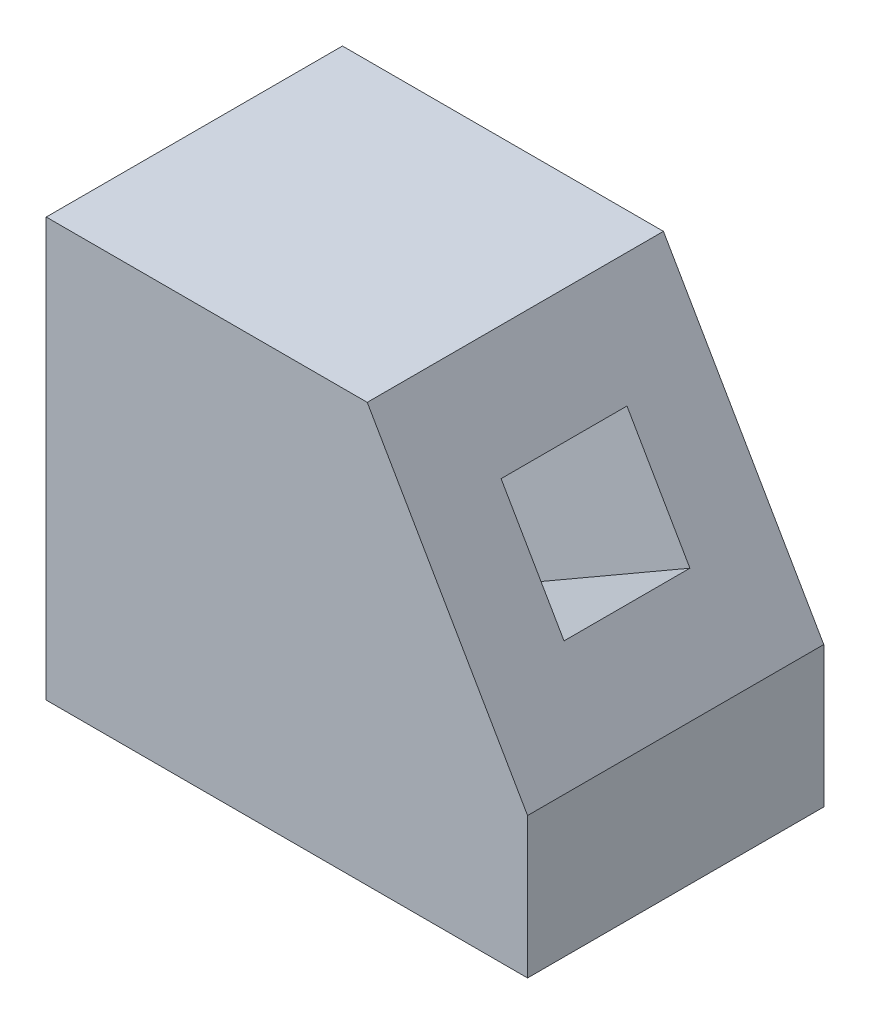
SolidWorks part; units mm, degrees
ref_plane "前视基准面" through (0, 0, 0) normal (0, 0, 1) x (1, 0, 0)
ref_plane "上视基准面" through (0, 0, 0) normal (0, 1, 0) x (1, 0, 0)
ref_plane "右视基准面" through (0, 0, 0) normal (1, 0, 0) x (0, 0, -1)
other "Configuration Table"
sketch "草图1" plane through (0, 0, 0) normal (0, 1, 0) x (1, 0, 0)
  line L0 (6.5, 0) -> (6.5, 8) construction
  line L1 (0, 0) -> (13, 0)
  line L2 (0, 0) -> (0, 8)
  line L3 (0, 8) -> (13, 8)
  line L4 (13, 0) -> (13, 8)
  dimension "D1" = 13
  dimension "D2" = 8
extrude "凸台-拉伸1" add sketch "草图1" along normal blind 11.3
sketch "草图2" plane through (0, 0, -8) normal (0, 0, -1) x (-1, 0, 0)
  line L0 (-13, 3.8) -> (-8.6699, 11.3)
  line L1 (-13, 11.3) -> (-13, 0) construction
  line L2 (-13, 11.3) -> (0, 11.3) construction
  line L3 (-8.6699, 11.3) -> (-13, 11.3)
  line L4 (-13, 11.3) -> (-13, 3.8)
  dimension "D1" = 30
  dimension "D2" = 7.5
extrude "切除-拉伸1" cut sketch "草图2" against normal up to next
sketch "草图3" plane through (11.3954, 6.5792, 0) normal (0.866, 0.5, 0) x (0, 0, -1)
  line L0 (0, 1.121) -> (8, 1.121) construction
  line L1 (0, 5.4512) -> (0, -3.2091) construction
  line L2 (8, -3.2091) -> (8, 5.4512) construction
  line L3 (4, 3.6037) -> (4, 7.0371) construction
  line L4 (5.7, 2.821) -> (2.3, 2.821)
  line L5 (2.3, 2.821) -> (2.3, -0.579)
  line L6 (5.7, 2.821) -> (5.7, -0.579)
  line L7 (5.7, -0.579) -> (2.3, -0.579)
  point P7 (4, 1.121)
  point P14 (4, 2.821)
  point P15 (5.7, 1.121)
  point P16 (2.3, 1.121)
  dimension "D1" = 1.7
  dimension "D2" = 1.7
extrude "切除-拉伸2" cut sketch "草图3" against normal blind 12
